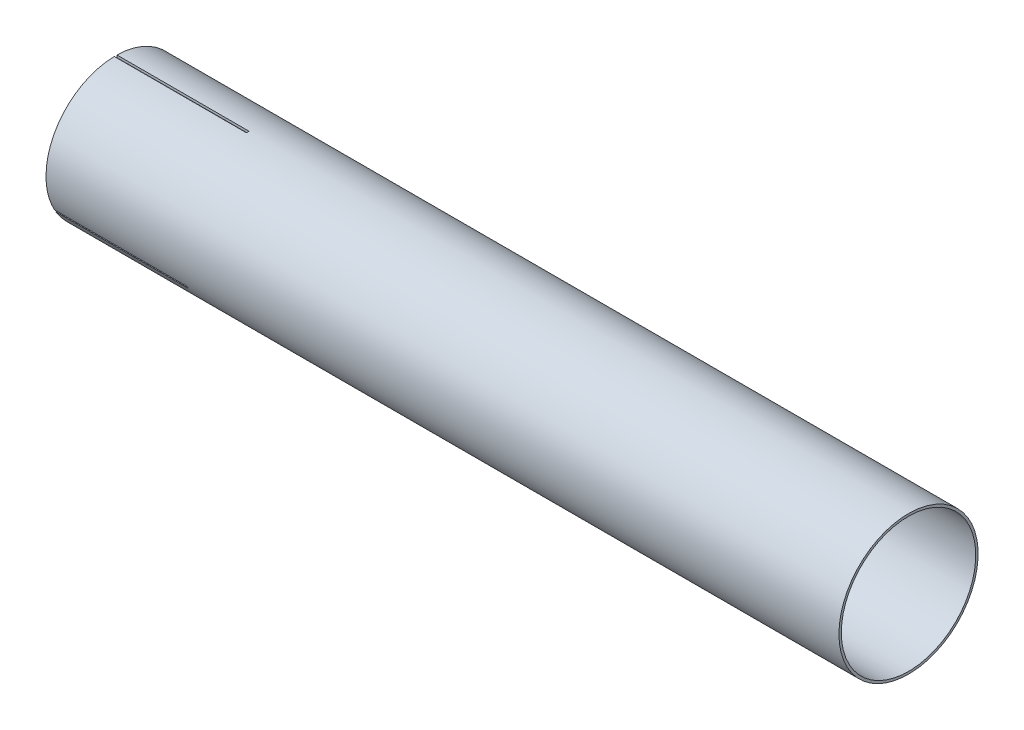
SolidWorks part; units mm, degrees
ref_plane "Plan de face" through (0, 0, 0) normal (0, 0, 1) x (1, 0, 0)
ref_plane "Plan de dessus" through (0, 0, 0) normal (0, 1, 0) x (1, 0, 0)
ref_plane "Plan de droite" through (0, 0, 0) normal (1, 0, 0) x (0, 0, -1)
sketch "Esquisse1" plane through (0, 0, 0) normal (0, 0, 1) x (1, 0, 0)
  line L0 (0, 0) -> (0, 79) construction
  line L1 (0, 0) -> (142.5133, 0) construction
  line L2 (0, 79) -> (900, 79)
  line L3 (0, 79) -> (0, -79) construction
  line L4 (0, 76.29) -> (900, 76.29)
  line L5 (900, 79) -> (900, 76.29)
  line L6 (0, -79) -> (900, -79) construction
  line L7 (0, 79) -> (0, 76.29)
  dimension "D1" = 158
  dimension "D2" = 152.58
  dimension "D3" = 900
revolve "Révolution1" add sketch "Esquisse1" angle 360 about L1
sketch "Esquisse2" plane through (0, 0, 0) normal (0, 1, 0) x (1, 0, 0)
  line L0 (0, 79) -> (0, -79) construction
  line L1 (0, -1.5) -> (150, -1.5)
  line L2 (0, -1.5) -> (0, 1.5)
  line L3 (0, 1.5) -> (150, 1.5)
  line L4 (150, -1.5) -> (150, 1.5)
  dimension "D1" = 3
  dimension "D2" = 150
extrude "Enlèv. mat.-Extru.1" cut sketch "Esquisse2" along normal through all
pattern_circular "Répétition circulaire1" count 3 over 240 about axis through (0, 0, 0) along (1, 0, 0) of "Enlèv. mat.-Extru.1"
